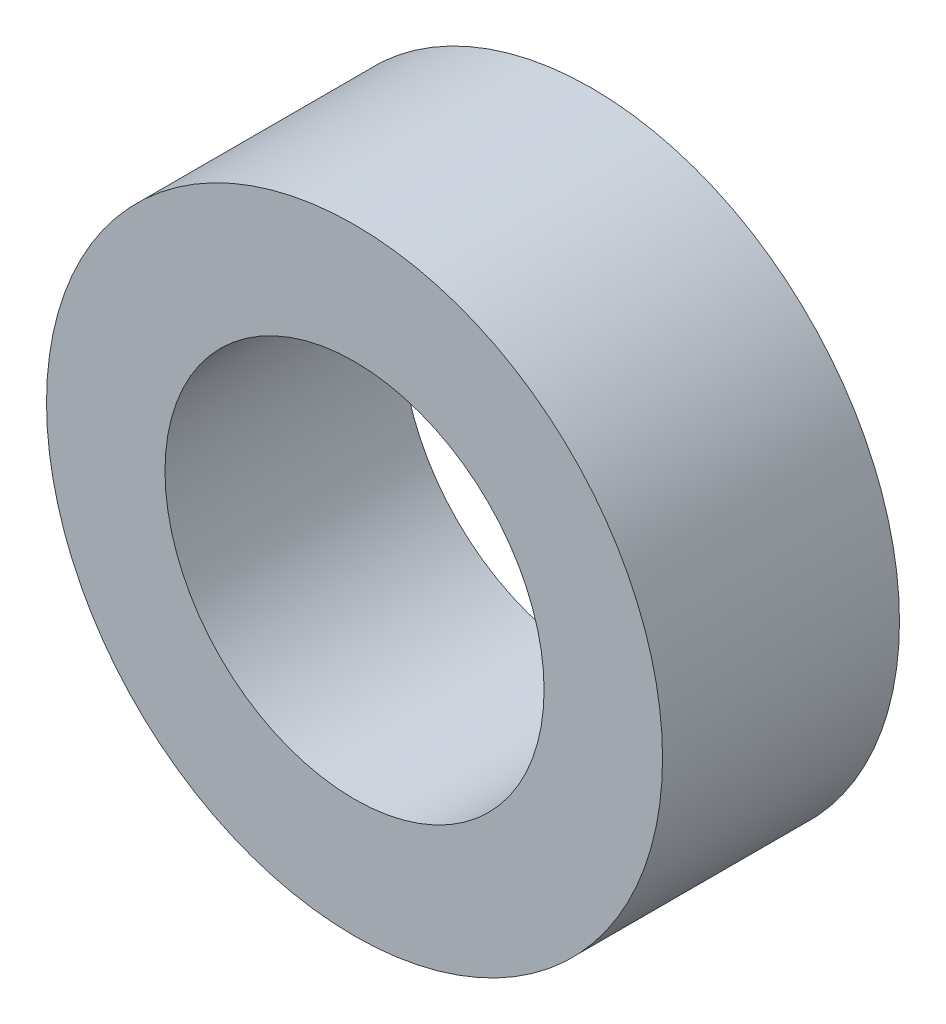
SolidWorks part; units mm, degrees
ref_plane "정면" through (0, 0, 0) normal (0, 0, 1) x (1, 0, 0)
ref_plane "윗면" through (0, 0, 0) normal (0, 1, 0) x (1, 0, 0)
ref_plane "우측면" through (0, 0, 0) normal (1, 0, 0) x (0, 0, -1)
sketch "스케치1" plane through (0, 0, 0) normal (0, 0, 1) x (1, 0, 0)
  circle A0 centre (0, 0) radius 8
  circle A1 centre (0, 0) radius 13
  dimension "D1" = 16
  dimension "D2" = 5
extrude "보스-돌출1" add sketch "스케치1" along normal blind 10
